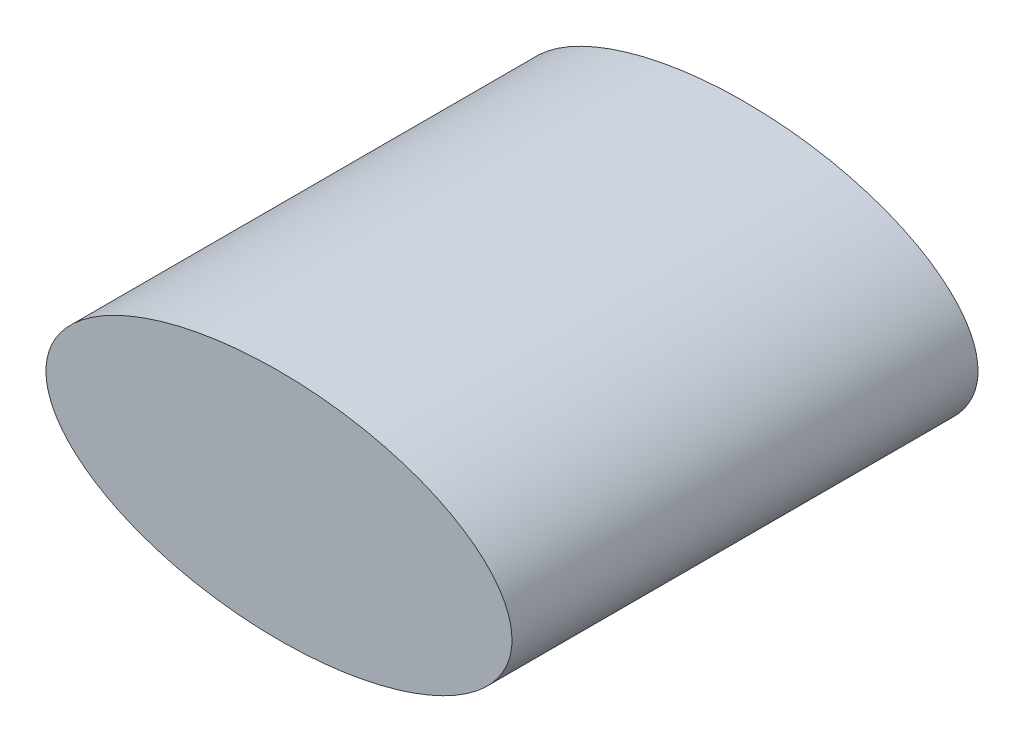
SolidWorks part; units mm, degrees
ref_plane "Front Plane" through (0, 0, 0) normal (0, 0, 1) x (1, 0, 0)
ref_plane "Top Plane" through (0, 0, 0) normal (0, 1, 0) x (1, 0, 0)
ref_plane "Right Plane" through (0, 0, 0) normal (1, 0, 0) x (0, 0, -1)
ref_plane "plane:profile-xy" through (0, 0, 0) normal (0, 0, 1) x (1, 0, 0)
sketch "sketch:main-profile" plane through (0, 0, 0) normal (0, 0, 1) x (1, 0, 0)
  ellipse E0 centre (0, 0) end of major axis (10, 0) minor radius 5
extrude "feature:ellipse-extrusion" add sketch "sketch:main-profile" along normal blind 20 separate body
